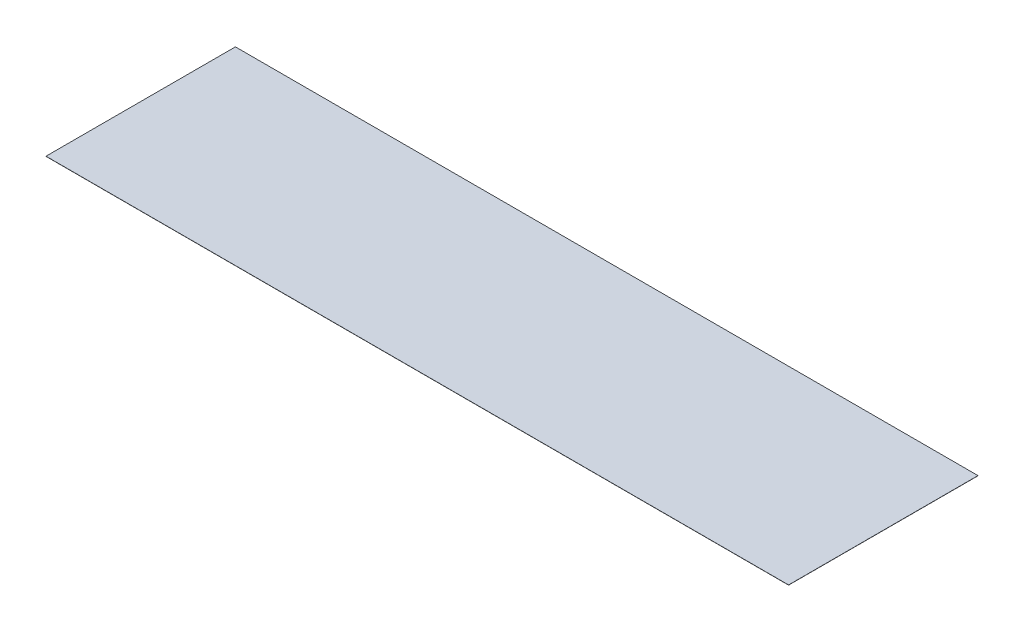
SolidWorks part; units mm, degrees
material "Sheet Moulding Compound"
ref_plane "Front Plane" through (0, 0, 0) normal (0, 0, 1) x (1, 0, 0)
ref_plane "Top Plane" through (0, 0, 0) normal (0, 1, 0) x (1, 0, 0)
ref_plane "Right Plane" through (0, 0, 0) normal (1, 0, 0) x (0, 0, -1)
sketch "Sketch1" plane through (0, 0, 0) normal (0, 1, 0) x (1, 0, 0)
  line L1 (0, 0) -> (321.5, 0)
  line L2 (0, 0) -> (0, 82)
  line L3 (0, 82) -> (321.5, 82)
  line L4 (321.5, 0) -> (321.5, 82)
  dimension "D1" = 82
  dimension "D2" = 321.5
extrude "Coating" add sketch "Sketch1" along normal blind 0.0762
